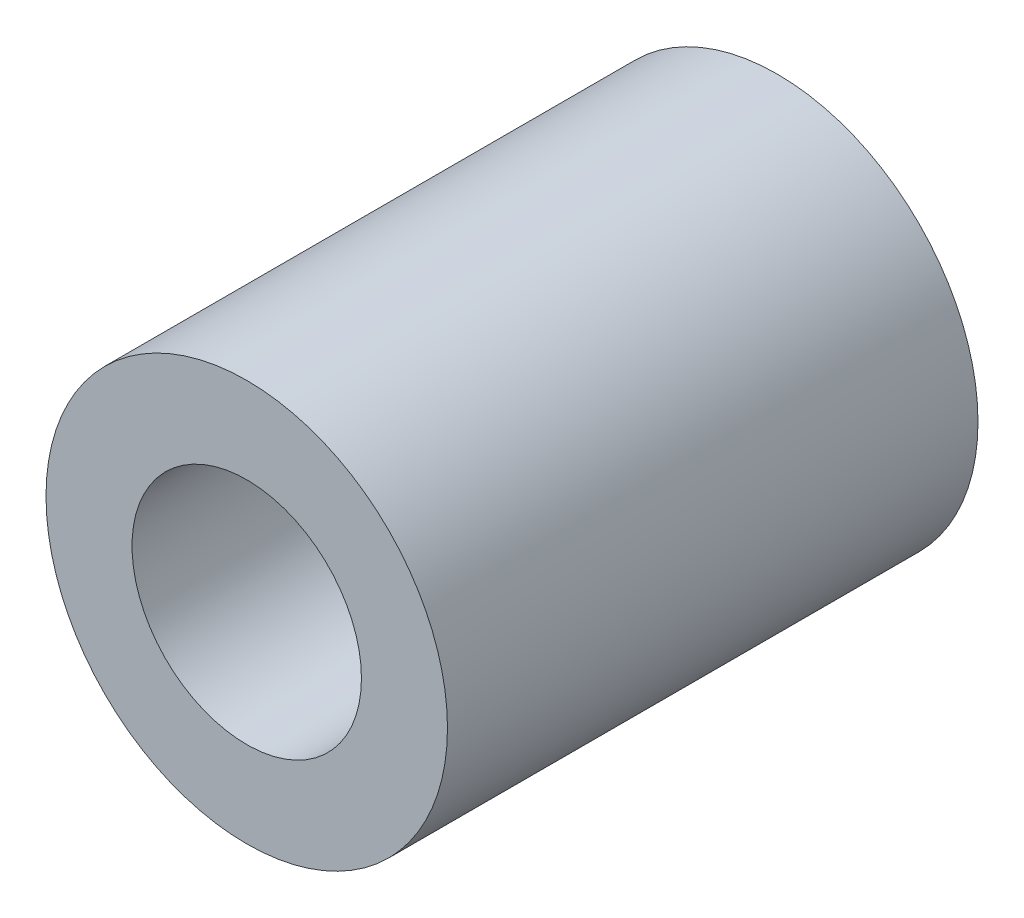
SolidWorks part; units mm, degrees
ref_plane "前视基准面" through (0, 0, 0) normal (0, 0, 1) x (1, 0, 0)
ref_plane "上视基准面" through (0, 0, 0) normal (0, 1, 0) x (1, 0, 0)
ref_plane "右视基准面" through (0, 0, 0) normal (1, 0, 0) x (0, 0, -1)
sketch "草图1" plane through (0, 0, 0) normal (0, 0, 1) x (1, 0, 0)
  circle A0 centre (0, 0) radius 8
  circle A1 centre (0, 0) radius 14
  dimension "D1" = 16
  dimension "D2" = 28
extrude "凸台-拉伸1" add sketch "草图1" along normal blind 37
